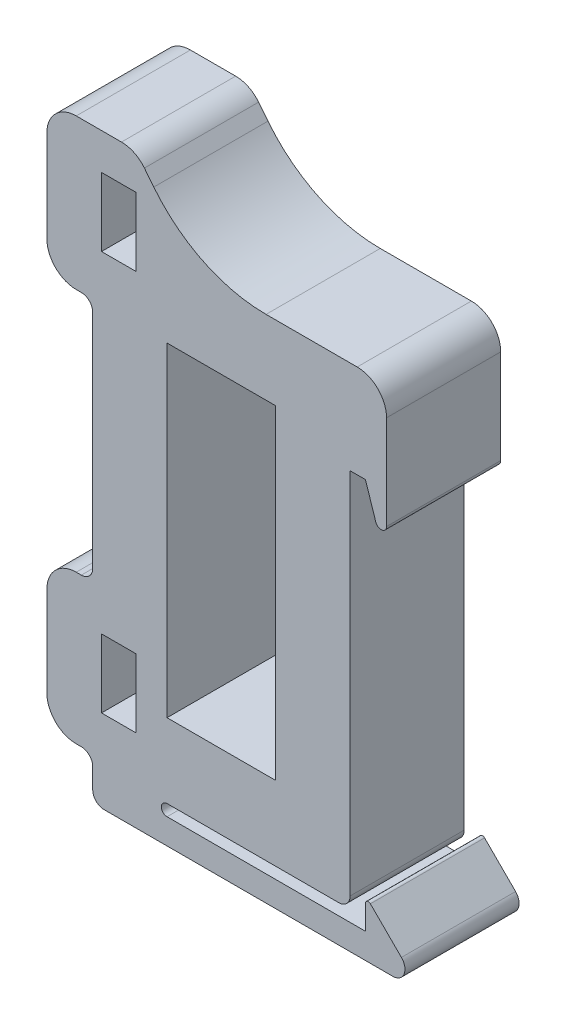
SolidWorks part; units mm, degrees
ref_plane "Front Plane" through (0, 0, 0) normal (0, 0, 1) x (1, 0, 0)
ref_plane "Top Plane" through (0, 0, 0) normal (0, 1, 0) x (1, 0, 0)
ref_plane "Right Plane" through (0, 0, 0) normal (1, 0, 0) x (0, 0, -1)
sketch "Sketch2" plane through (0, 0, 0) normal (0, 0, 1) x (1, 0, 0)
  line L26 (0, 66.6518) -> (0, 33.3918)
  line L27 (0, 66.6518) -> (1.3474, 66.6518)
  line L29 (3.1939, 72.2618) -> (3.1939, 64.0167)
  line L30 (1.3474, 66.6518) -> (2.26, 63.8675)
  line L32 (-22.54, 67.4018) -> (-22.54, 47.9618)
  line L33 (0, 33.3918) -> (-16.03, 33.3918)
  line L34 (-16.03, 68.3218) -> (-6.51, 68.3218)
  line L35 (-16.03, 68.3218) -> (-16.03, 39.9018)
  line L36 (-16.03, 39.9018) -> (-6.51, 39.9018)
  line L37 (-6.51, 68.3218) -> (-6.51, 39.9018)
  line L39 (1.3522, 32.3918) -> (1.3522, 34.5182)
  line L40 (1.7789, 34.6951) -> (4.4968, 31.982)
  line L42 (3.7479, 30.1718) -> (-21.54, 30.1718)
  line L43 (1.3522, 32.3918) -> (-16.03, 32.3918)
  line L47 (-22.54, 32.9426) -> (-22.54, 31.1718)
  line L48 (-21.7699, 78.3926) -> (-21.7699, 72.3926)
  line L49 (-21.7699, 37.3926) -> (-18.7599, 37.3926)
  line L50 (-18.7599, 37.3926) -> (-18.7599, 43.3926)
  line L51 (-18.7599, 78.3926) -> (-21.7699, 78.3926)
  line L52 (-23.54, 68.4018) -> (-23.9846, 68.4018)
  line L54 (-26.5546, 77.4018) -> (-26.5546, 70.9718)
  line L55 (-21.7699, 72.3926) -> (-18.7599, 72.3926)
  line L56 (-21.7699, 43.3926) -> (-21.7699, 37.3926)
  line L57 (-21.7699, 43.3926) -> (-18.7599, 43.3926)
  line L58 (-18.7599, 72.3926) -> (-18.7599, 78.3926)
  line L60 (-26.5546, 44.3918) -> (-26.5546, 36.5126)
  line L65 (-26.5546, 77.4018) -> (-26.5546, 79.0009)
  line L71 (-23.9846, 81.5709) -> (-20.0216, 81.5709)
  line L73 (0.6239, 74.8318) -> (-7.3575, 74.8318)
  line L74 (-17.1909, 79.5718) -> (-18.0111, 80.6018)
  line L76 (-23.9846, 46.9618) -> (-23.54, 46.9618)
  line L78 (-23.9846, 33.9426) -> (-23.54, 33.9426)
  arc A1 (1.7789, 34.6951) -> (1.3522, 34.5182) centre (1.6022, 34.5182) ccw
  arc A2 (3.7479, 30.1718) -> (4.4968, 31.982) centre (3.7479, 31.2318) ccw
  arc A4 (2.26, 63.8675) -> (3.1939, 64.0167) centre (2.715, 64.0167) ccw
  arc A6 (-16.03, 33.3918) -> (-16.03, 32.3918) centre (-16.03, 32.8918) ccw
  arc A7 (-18.0111, 80.6018) -> (-20.0216, 81.5709) centre (-20.0216, 79.0009) ccw
  arc A8 (-7.3575, 74.8318) -> (-17.1909, 79.5718) centre (-7.3575, 87.4018) cw
  arc A9 (0.6239, 74.8318) -> (3.1939, 72.2618) centre (0.6239, 72.2618) cw
  arc A10 (-26.5546, 79.0009) -> (-23.9846, 81.5709) centre (-23.9846, 79.0009) cw
  arc A11 (-23.9846, 68.4018) -> (-26.5546, 70.9718) centre (-23.9846, 70.9718) cw
  arc A12 (-22.54, 67.4018) -> (-23.54, 68.4018) centre (-23.54, 67.4018) ccw
  arc A13 (-26.5546, 44.3918) -> (-23.9846, 46.9618) centre (-23.9846, 44.3918) cw
  arc A14 (-23.9846, 33.9426) -> (-26.5546, 36.5126) centre (-23.9846, 36.5126) cw
  arc A15 (-23.54, 33.9426) -> (-22.54, 32.9426) centre (-23.54, 32.9426) cw
  arc A16 (-22.54, 31.1718) -> (-21.54, 30.1718) centre (-21.54, 31.1718) ccw
  arc A17 (-22.54, 47.9618) -> (-23.54, 46.9618) centre (-23.54, 47.9618) cw
  point P38 (-21.7699, 40.3926)
  point P46 (-21.7699, 75.3926)
  dimension "D6" = 0.25
  dimension "D7" = 1.06
  dimension "D13" = 12.57
  dimension "D10" = 2.57
  dimension "D15" = 2.57
  dimension "D16" = 2.57
  dimension "D17" = 2.57
  dimension "D18" = 1
  dimension "D19" = 2.57
  dimension "D20" = 2.57
  dimension "D21" = 1
  dimension "D22" = 1
  dimension "D1" = 2.26
  dimension "D2" = 6.51
  dimension "D3" = 6.51
  dimension "D4" = 6.51
  dimension "D5" = 9.52
  dimension "D8" = 6.51
  dimension "D9" = 1
  dimension "D11" = 28.42
  dimension "D12" = 33.26
  dimension "D14" = 35
extrude "Boss-Extrude1" add sketch "Sketch2" along normal blind 10
sketch "Sketch3" plane through (-26.5546, 0, 0) normal (-1, 0, 0) x (0, 0, 1)
  line L0 (0, 74.9863) -> (10, 74.9863) construction
  line L1 (0, 79.0009) -> (0, 70.9718) construction
  line L2 (10, 79.0009) -> (10, 70.9718) construction
  line L3 (10, 74.9863) -> (5, 79.0009) construction
  line L4 (10, 79.0009) -> (0, 79.0009) construction
  line L5 (5, 79.0009) -> (5, 70.9718) construction
  line L6 (10, 70.9718) -> (0, 70.9718) construction
  line L7 (5, 70.9718) -> (5, 36.5126) construction
  line L8 (10, 36.5126) -> (0, 36.5126) construction
  line L9 (5, 36.5126) -> (10, 40.4522) construction
  line L10 (10, 44.3918) -> (10, 36.5126) construction
  line L11 (10, 40.4522) -> (0, 40.4522) construction
  line L12 (0, 44.3918) -> (0, 36.5126) construction
  line L13 (0, 40.4522) -> (5, 44.3918) construction
  circle A0 centre (5, 40.4522) radius 1.9686
  circle A1 centre (5, 74.9863) radius 1.9686
extrude "Cut-Extrude1" cut sketch "Sketch3" against normal blind 9
fillet "Fillet1" radius 1 1 edges at (0, 33.3918, 5)
